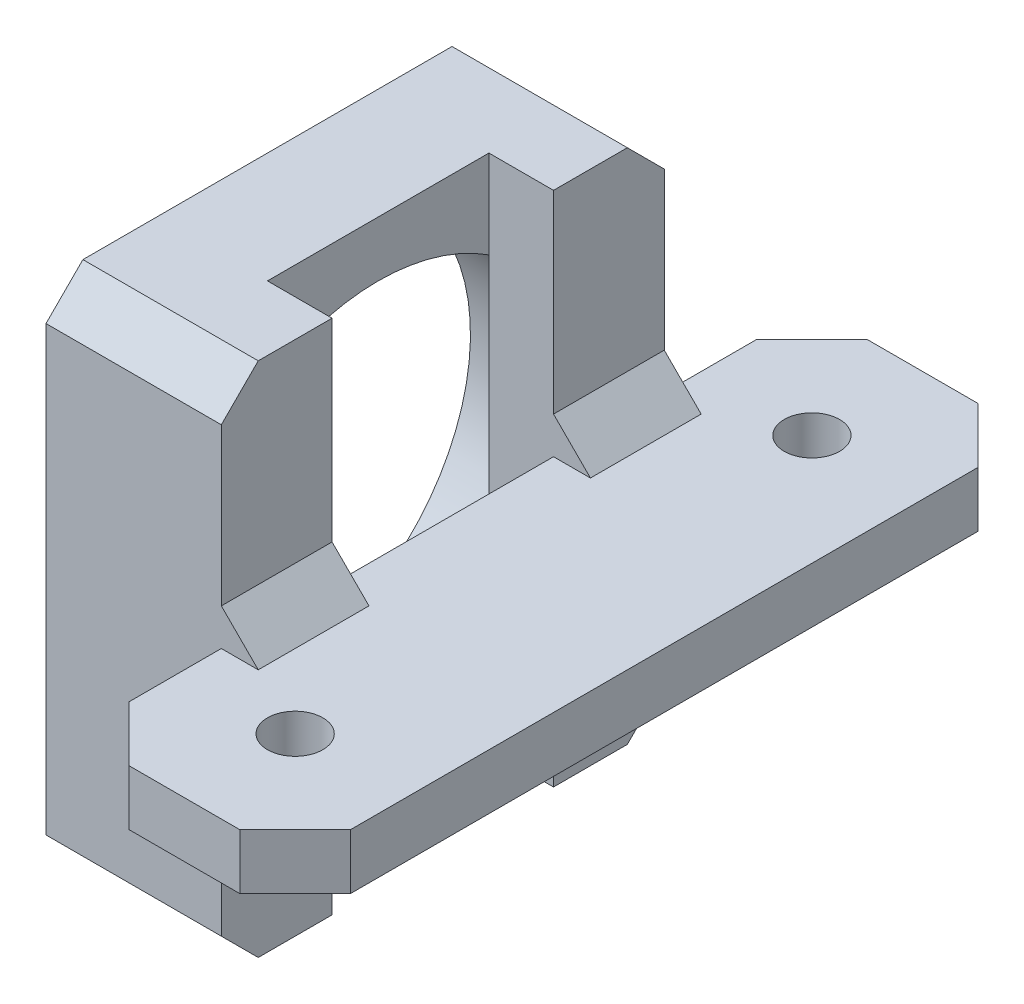
SolidWorks part; units mm, degrees
ref_plane "Front Plane" through (0, 0, 0) normal (0, 0, 1) x (1, 0, 0)
ref_plane "Top Plane" through (0, 0, 0) normal (0, 1, 0) x (1, 0, 0)
ref_plane "Right Plane" through (0, 0, 0) normal (1, 0, 0) x (0, 0, -1)
sketch "Sketch1" plane through (0, 0, 0) normal (0, 1, 0) x (1, 0, 0)
  line L0 (-6, 17) -> (-3, 20)
  line L1 (-3, 20) -> (3, 20)
  line L2 (-6, 17) -> (-6, -17)
  line L3 (-3, -20) -> (3, -20)
  line L4 (6, 17) -> (6, -17)
  line L5 (-6, 20) -> (6, -20) construction
  line L6 (-6, -20) -> (6, 20) construction
  line L7 (3, 20) -> (6, 17)
  line L8 (-6, -17) -> (-3, -20)
  line L9 (3, -20) -> (6, -17)
  circle A0 centre (0, 14) radius 1.5
  circle A1 centre (0, -14) radius 1.5
  point P0 (0, 0)
  dimension "D3" = 3
  dimension "D1" = 40
  dimension "D2" = 12
  dimension "D4" = 28
  dimension "D9" = 14
extrude "Boss-Extrude1" add sketch "Sketch1" along normal blind 3 contours A0 | L2 L8 L3 L9 L4 L7 L1 L0 | A1
sketch "Sketch2" plane through (0, 3, 0) normal (0, 1, 0) x (1, 0, 0)
  line L1 (-9.5, 12) -> (-6, 12)
  line L2 (-9.5, 12) -> (-9.5, 6)
  line L3 (-9.5, 6) -> (-6, 6)
  line L4 (-6, 12) -> (-6, 6)
  line L5 (-3, -20) -> (3, -20) construction
  line L6 (-9.5, -6) -> (-6, -6)
  line L7 (-9.5, -6) -> (-9.5, -12)
  line L8 (-9.5, -12) -> (-6, -12)
  line L9 (-6, -6) -> (-6, -12)
  line L10 (-3, 20) -> (3, 20) construction
  line L11 (-6, 17) -> (-6, -17) construction
  dimension "D1" = 6
  dimension "D2" = 6
  dimension "D3" = 8
  dimension "D4" = 8
  dimension "D5" = 3.5
  dimension "D6" = 3.5
extrude "Boss-Extrude2" add sketch "Sketch2" against normal blind 28 from offset 12.5 contours L2 L1 L4 L3 | L9 L8 L7 L6
chamfer "Chamfer2" distance 2 4 edges at (-6, 0, -9) (-6, 0, 9) (-6, 3, -9) (-6, 3, 9)
sketch "Sketch3" plane through (-9.5, 0, 0) normal (-1, 0, 0) x (0, 0, 1)
  line L1 (-12, 15.5) -> (12, 15.5)
  line L2 (-12, 15.5) -> (-12, -12.5)
  line L3 (-12, -12.5) -> (12, -12.5)
  line L4 (12, 15.5) -> (12, -12.5)
  circle A0 centre (0, 1.5) radius 11
  point P9 (0, 15.5)
  point P11 (-12, 1.5)
  dimension "D1" = 22
extrude "Boss-Extrude4" add sketch "Sketch3" along normal blind 6
chamfer "Chamfer3" distance 2 angle 45 4 edges at (-10.75, 15.5, -12) (-10.75, -12.5, -12) (-10.75, 15.5, 12) (-10.75, -12.5, 12)
